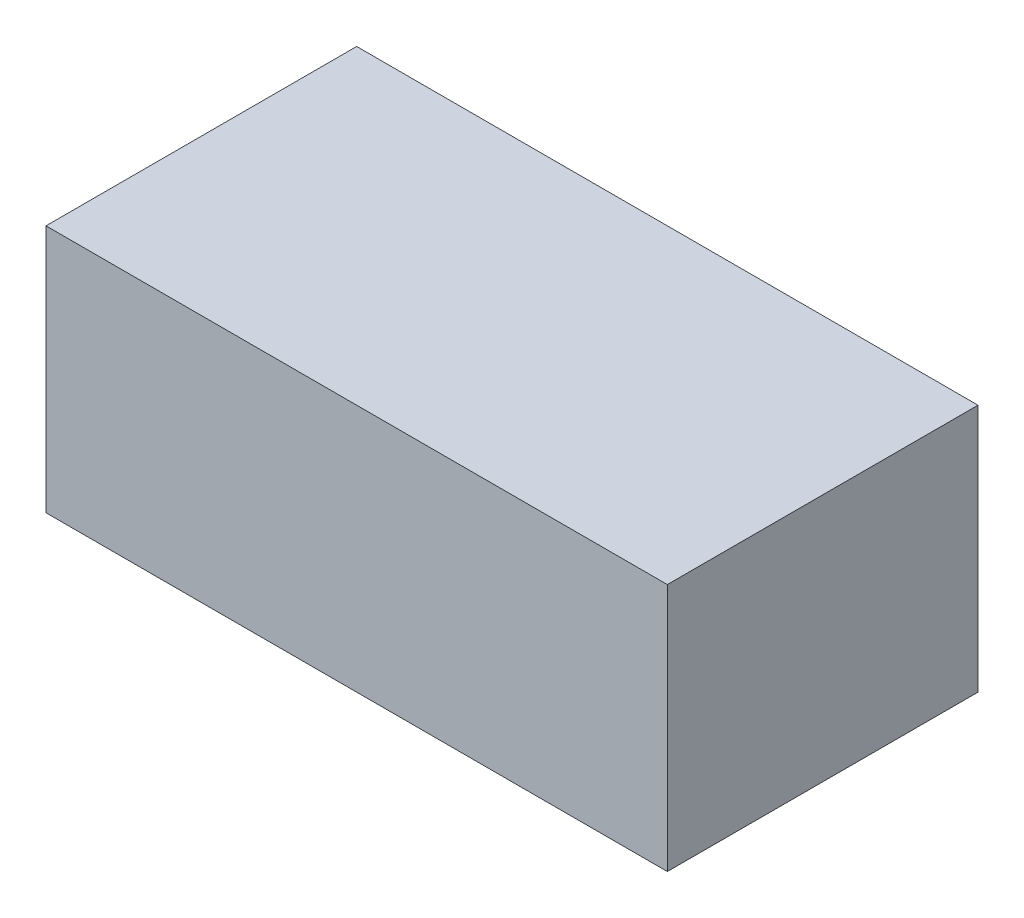
SolidWorks part; units mm, degrees
ref_plane "Plan1" through (0, 0, 0) normal (0, 0, 1) x (1, 0, 0)
ref_plane "Plan2" through (0, 0, 0) normal (0, 1, 0) x (1, 0, 0)
ref_plane "Plan3" through (0, 0, 0) normal (1, 0, 0) x (0, 0, -1)
sketch "Esquisse1" plane through (0, 0, 0) normal (0, 0, 1) x (1, 0, 0)
  line L1 (0, 0) -> (30, 0)
  line L2 (0, 0) -> (0, 12)
  line L3 (0, 12) -> (30, 12)
  line L4 (30, 0) -> (30, 12)
  dimension "D1" = 12
extrude "Base-Extrusion" add sketch "Esquisse1" along normal blind 15
